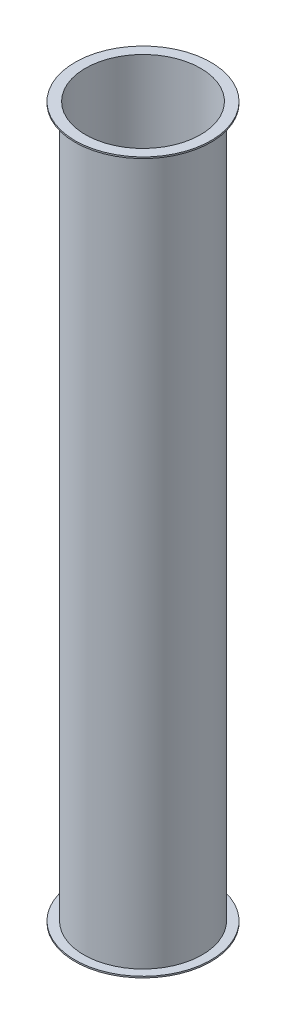
SolidWorks part; units mm, degrees
material "AISI 304"
ref_plane "Piano frontale" through (0, 0, 0) normal (0, 0, 1) x (1, 0, 0)
ref_plane "Piano superiore" through (0, 0, 0) normal (0, 1, 0) x (1, 0, 0)
ref_plane "Piano destro" through (0, 0, 0) normal (1, 0, 0) x (0, 0, -1)
sketch "Schizzo1" plane through (0, 0, 0) normal (0, 1, 0) x (1, 0, 0)
  circle A0 centre (0, 0) radius 40
extrude "Estrusione-Sottile1" add sketch "Schizzo1" along normal blind 481.5 thin thin type one direction reverse wall 1
sketch "Schizzo2" plane through (0, 481.5, 0) normal (0, 1, 0) x (1, 0, 0)
  circle A0 centre (0, 0) radius 40 construction
  circle A1 centre (0, 0) radius 40
  circle A2 centre (0, 0) radius 46
  dimension "D1" = 6
extrude "Estrusione-Estrusione1" add sketch "Schizzo2" against normal blind 1
sketch "Schizzo3" plane through (0, 0, 0) normal (0, -1, 0) x (1, 0, 0)
  circle A0 centre (0, 0) radius 40 construction
  circle A1 centre (0, 0) radius 40
  circle A2 centre (0, 0) radius 46
  dimension "D1" = 6
extrude "Estrusione-Estrusione2" add sketch "Schizzo3" against normal blind 1
sketch "Schizzo4" plane through (0, 0, 0) normal (0, -1, 0) x (1, 0, 0)
  circle A0 centre (0, 0) radius 42 construction
